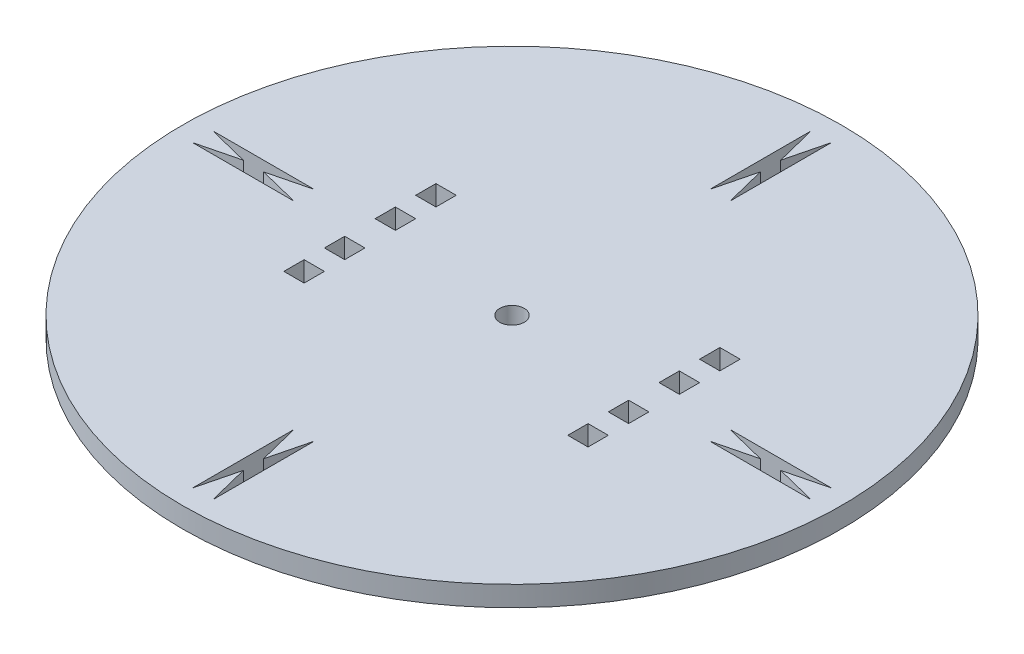
SolidWorks part; units mm, degrees
ref_plane "Front Plane" through (0, 0, 0) normal (0, 0, 1) x (1, 0, 0)
ref_plane "Top Plane" through (0, 0, 0) normal (0, 1, 0) x (1, 0, 0)
ref_plane "Right Plane" through (0, 0, 0) normal (1, 0, 0) x (0, 0, -1)
sketch "Sketch1" plane through (0, 0, 0) normal (0, 1, 0) x (1, 0, 0)
  line L0 (-36.1983, 111.6242) -> (-36.1983, -53.4758) construction
  line L1 (-118.7483, 29.0742) -> (46.3517, 29.0742) construction
  line L2 (-36.1983, 96.3842) -> (-33.6583, 106.5442)
  line L3 (-33.6583, 106.5442) -> (-33.6583, 81.1442)
  line L4 (-33.6583, 81.1442) -> (-36.1983, 91.3042)
  line L5 (-38.7383, 81.1442) -> (-36.1983, 91.3042)
  line L6 (-38.7383, 106.5442) -> (-38.7383, 81.1442)
  line L7 (-36.1983, 96.3842) -> (-38.7383, 106.5442)
  line L8 (31.1117, 29.0742) -> (41.2717, 26.5342)
  line L9 (41.2717, 26.5342) -> (15.8717, 26.5342)
  line L10 (15.8717, 26.5342) -> (26.0317, 29.0742)
  line L11 (15.8717, 31.6142) -> (26.0317, 29.0742)
  line L12 (41.2717, 31.6142) -> (15.8717, 31.6142)
  line L13 (31.1117, 29.0742) -> (41.2717, 31.6142)
  line L14 (-36.1983, -38.2358) -> (-38.7383, -48.3958)
  line L15 (-38.7383, -48.3958) -> (-38.7383, -22.9958)
  line L16 (-38.7383, -22.9958) -> (-36.1983, -33.1558)
  line L17 (-33.6583, -22.9958) -> (-36.1983, -33.1558)
  line L18 (-33.6583, -48.3958) -> (-33.6583, -22.9958)
  line L19 (-36.1983, -38.2358) -> (-33.6583, -48.3958)
  line L20 (-103.5083, 29.0742) -> (-113.6683, 31.6142)
  line L21 (-113.6683, 31.6142) -> (-88.2683, 31.6142)
  line L22 (-88.2683, 31.6142) -> (-98.4283, 29.0742)
  line L23 (-88.2683, 26.5342) -> (-98.4283, 29.0742)
  line L24 (-113.6683, 26.5342) -> (-88.2683, 26.5342)
  line L25 (-103.5083, 29.0742) -> (-113.6683, 26.5342)
  circle A0 centre (-36.1983, 29.0742) radius 82.55
  circle A1 centre (-36.1983, 29.0742) radius 3.048
  point P7 (-36.1983, 29.0742)
  point P34 (-36.1983, 29.0742)
  dimension "D1" = 165.1
  dimension "D8" = 6.096
  dimension "D2" = 2.54
  dimension "D3" = 10.16
  dimension "D4" = 10.16
  dimension "D5" = 25.4
  dimension "D6" = 52.07
  dimension "D7" = 4
extrude "Boss-Extrude1" add sketch "Sketch1" along normal blind 5.08
sketch "Sketch2" plane through (0, 5.08, 0) normal (0, 1, 0) x (1, 0, 0)
  line L0 (-36.1983, 111.6242) -> (-36.1983, -53.4758) construction
  line L1 (46.3517, 29.0742) -> (-118.7483, 29.0742) construction
  line L2 (-74.2983, 111.6242) -> (-74.2983, -53.4758) construction
  line L3 (1.9017, 111.6242) -> (1.9017, -53.4758) construction
  line L4 (-136.2937, 48.1242) -> (91.435, 48.1242) construction
  line L5 (-3.1783, 25.2642) -> (-3.1783, 20.1842)
  line L6 (1.9017, 43.0442) -> (-3.1783, 43.0442)
  line L7 (1.9017, 43.0442) -> (1.9017, 48.1242)
  line L8 (1.9017, 48.1242) -> (-3.1783, 48.1242)
  line L9 (-3.1783, 43.0442) -> (-3.1783, 48.1242)
  line L10 (1.9017, 32.8842) -> (-3.1783, 32.8842)
  line L11 (1.9017, 32.8842) -> (1.9017, 37.9642)
  line L12 (1.9017, 37.9642) -> (-3.1783, 37.9642)
  line L13 (-3.1783, 32.8842) -> (-3.1783, 37.9642)
  line L14 (1.9017, 20.1842) -> (-3.1783, 20.1842)
  line L15 (1.9017, 25.2642) -> (1.9017, 20.1842)
  line L16 (1.9017, 25.2642) -> (-3.1783, 25.2642)
  line L17 (-3.1783, 15.1042) -> (-3.1783, 10.0242)
  line L18 (1.9017, 10.0242) -> (-3.1783, 10.0242)
  line L19 (1.9017, 15.1042) -> (1.9017, 10.0242)
  line L20 (1.9017, 15.1042) -> (-3.1783, 15.1042)
  line L21 (-74.2983, 15.1042) -> (-69.2183, 15.1042)
  line L22 (-74.2983, 15.1042) -> (-74.2983, 10.0242)
  line L23 (-74.2983, 10.0242) -> (-69.2183, 10.0242)
  line L24 (-69.2183, 15.1042) -> (-69.2183, 10.0242)
  line L25 (-74.2983, 25.2642) -> (-69.2183, 25.2642)
  line L26 (-74.2983, 25.2642) -> (-74.2983, 20.1842)
  line L27 (-74.2983, 20.1842) -> (-69.2183, 20.1842)
  line L28 (-69.2183, 32.8842) -> (-69.2183, 37.9642)
  line L29 (-74.2983, 37.9642) -> (-69.2183, 37.9642)
  line L30 (-74.2983, 32.8842) -> (-74.2983, 37.9642)
  line L31 (-74.2983, 32.8842) -> (-69.2183, 32.8842)
  line L32 (-69.2183, 43.0442) -> (-69.2183, 48.1242)
  line L33 (-74.2983, 48.1242) -> (-69.2183, 48.1242)
  line L34 (-74.2983, 43.0442) -> (-74.2983, 48.1242)
  line L35 (-74.2983, 43.0442) -> (-69.2183, 43.0442)
  line L36 (-69.2183, 25.2642) -> (-69.2183, 20.1842)
  circle A0 centre (-36.1983, 29.0742) radius 82.55 construction
  dimension "D3" = 19.05
  dimension "D4" = 5.08
  dimension "D5" = 5.08
  dimension "D6" = 5.08
  dimension "D7" = 5.08
  dimension "D8" = 5.08
  dimension "D2" = 3.81
  dimension "D1" = 38.1
extrude "Cut-Extrude1" cut sketch "Sketch2" against normal blind 5.08
sketch "Sketch3" plane through (0, 5.08, 0) normal (0, 1, 0) x (1, 0, 0)
  line L0 (-36.1983, 111.6242) -> (-36.1983, -53.4758)
  line L1 (46.3517, 29.0742) -> (-118.7483, 29.0742)
  circle A0 centre (-36.1983, 29.0742) radius 82.55 construction
